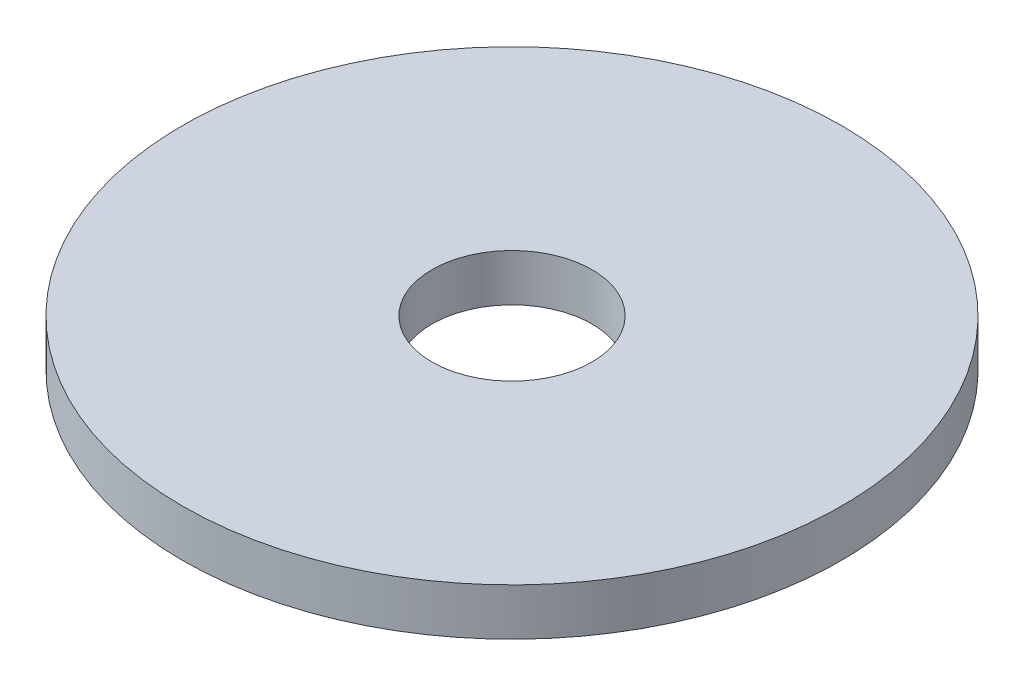
SolidWorks part; units mm, degrees
ref_plane "Płaszczyzna przednia" through (0, 0, 0) normal (0, 0, 1) x (1, 0, 0)
ref_plane "Płaszczyzna górna" through (0, 0, 0) normal (0, 1, 0) x (1, 0, 0)
ref_plane "Płaszczyzna prawa" through (0, 0, 0) normal (1, 0, 0) x (0, 0, -1)
sketch "Szkic1" plane through (0, 0, 0) normal (0, 1, 0) x (1, 0, 0)
  circle A0 centre (0, 0) radius 35
  circle A1 centre (0, 0) radius 8.5
extrude "Dodanie-wyciągnięcie1" add sketch "Szkic1" along normal blind 5
